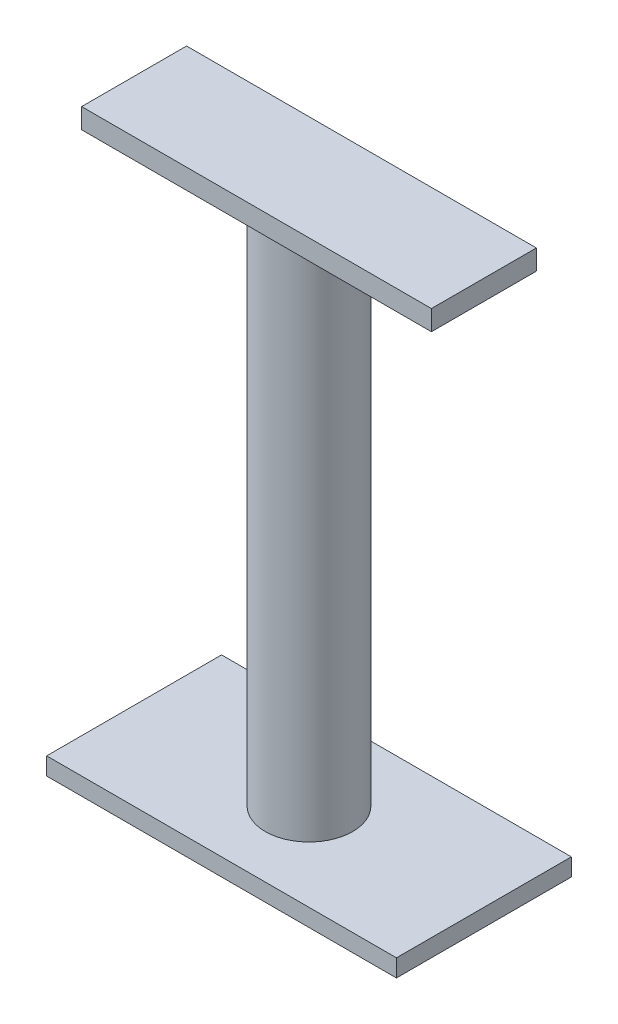
SolidWorks part; units mm, degrees
ref_plane "前视基准面" through (0, 0, 0) normal (0, 0, 1) x (1, 0, 0)
ref_plane "上视基准面" through (0, 0, 0) normal (0, 1, 0) x (1, 0, 0)
ref_plane "右视基准面" through (0, 0, 0) normal (1, 0, 0) x (0, 0, -1)
sketch "草图6" plane through (0, 0, 0) normal (0, 1, 0) x (1, 0, 0)
  line L0 (-100, -50) -> (100, -50)
  line L1 (100, -50) -> (100, 50)
  line L2 (100, 50) -> (-100, 50)
  line L3 (-100, 50) -> (-100, -50)
extrude "Base Plate" add sketch "草图6" along normal blind 10 from offset 160
sketch "草图7" plane through (0, 0, 0) normal (0, 1, 0) x (1, 0, 0)
  circle A0 centre (0, 0) radius 25
  dimension "PostDiameter" = 50
extrude "Post" add sketch "草图7" along normal blind 300 from offset 150
sketch "草图8" plane through (0, 0, 0) normal (0, 1, 0) x (1, 0, 0)
  line L0 (-100, -30) -> (100, -30)
  line L1 (100, -30) -> (100, 30)
  line L2 (100, 30) -> (-100, 30)
  line L3 (-100, 30) -> (-100, -30)
extrude "Top Plate" add sketch "草图8" along normal blind 11.5 from offset 150
